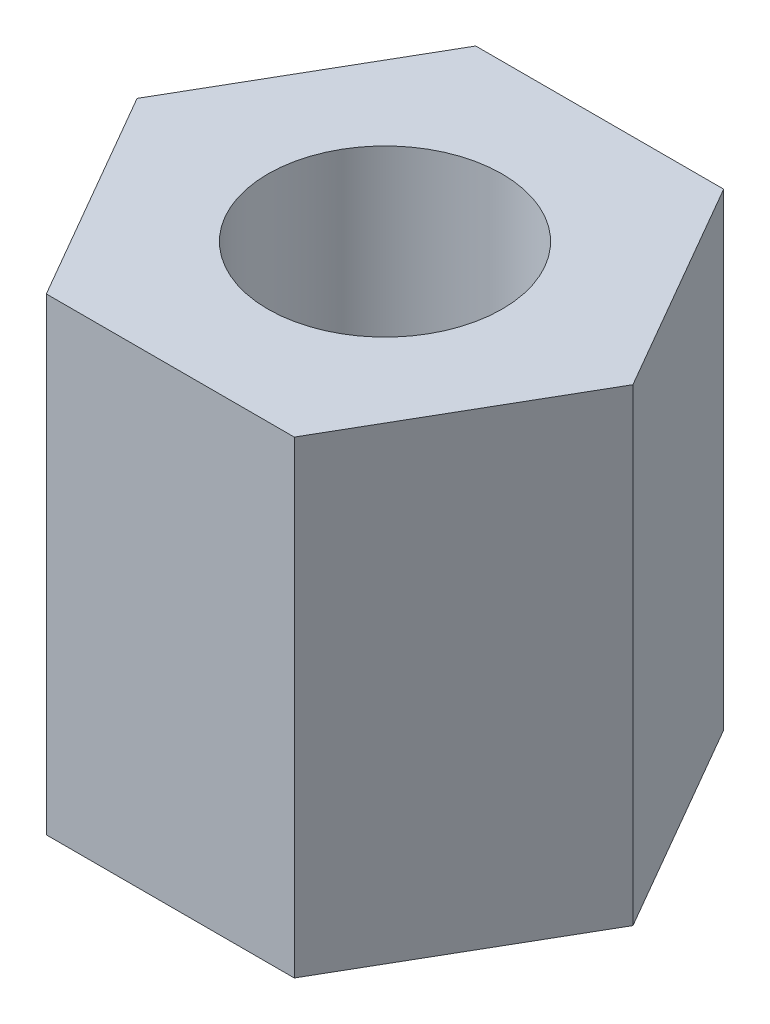
SolidWorks part; units mm, degrees
material "黄铜"
ref_plane "前视基准面" through (0, 0, 0) normal (0, 0, 1) x (1, 0, 0)
ref_plane "上视基准面" through (0, 0, 0) normal (0, 1, 0) x (1, 0, 0)
ref_plane "右视基准面" through (0, 0, 0) normal (1, 0, 0) x (0, 0, -1)
other "Configuration Table"
sketch "草图1" plane through (0, 0, 0) normal (0, 1, 0) x (1, 0, 0)
  line L1 (3.1754, 0) -> (1.5877, 2.75)
  line L2 (1.5877, 2.75) -> (-1.5877, 2.75)
  line L3 (-1.5877, 2.75) -> (-3.1754, 0)
  line L4 (-3.1754, 0) -> (-1.5877, -2.75)
  line L5 (-1.5877, -2.75) -> (1.5877, -2.75)
  line L6 (1.5877, -2.75) -> (3.1754, 0)
  circle A0 centre (0, 0) radius 2.75 construction
  circle A1 centre (0, 0) radius 1.5
  dimension "D1" = 5.5
  dimension "D2" = 3
extrude "凸台-拉伸1" add sketch "草图1" along normal blind 6
